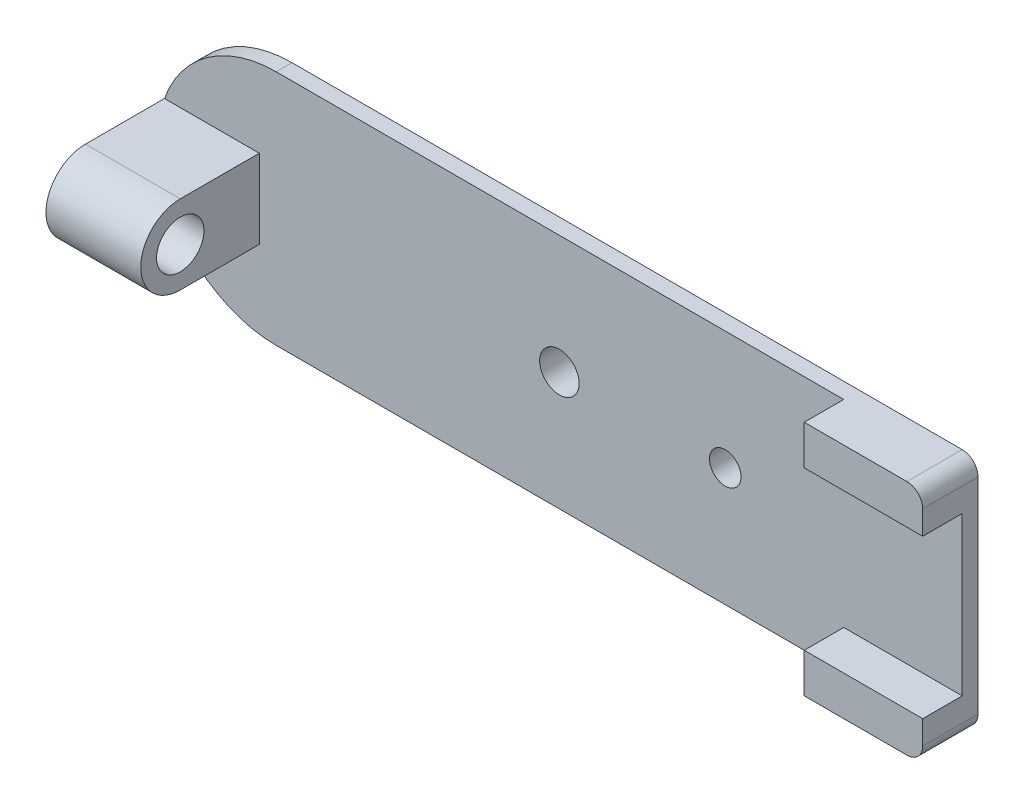
SolidWorks part; units mm, degrees
ref_plane "FACE" through (0, 0, 0) normal (0, 0, 1) x (1, 0, 0)
ref_plane "DESSSUS" through (0, 0, 0) normal (0, 1, 0) x (1, 0, 0)
ref_plane "DROITE" through (0, 0, 0) normal (1, 0, 0) x (0, 0, -1)
sketch "Esquisse1" plane through (0, 0, 0) normal (0, 0, 1) x (1, 0, 0)
  line L0 (0, 30) -> (173.7157, 30)
  line L1 (173.7157, 30) -> (173.7157, -30)
  line L2 (173.7157, -30) -> (0, -30)
  line L3 (-28.2843, 10) -> (-28.2843, -10)
  arc A0 (0, 30) -> (-28.2843, 10) centre (0, 0) ccw
  arc A1 (-28.2843, -10) -> (0, -30) centre (0, 0) ccw
  dimension "D1" = 60
  dimension "D2" = 20
  dimension "D3" = 202
extrude "Base-Extrusion" add sketch "Esquisse1" along normal blind 4
sketch "Esquisse2" plane through (0, 0, 4) normal (0, 0, 1) x (1, 0, 0)
  line L0 (173.7157, 30) -> (0, 30) construction
  line L1 (143.7157, 30) -> (173.7157, 30)
  line L2 (143.7157, 30) -> (143.7157, 20)
  line L3 (143.7157, 20) -> (173.7157, 20)
  line L4 (173.7157, 30) -> (173.7157, 20)
  line L5 (173.7157, -30) -> (173.7157, 30) construction
  line L6 (0, -30) -> (173.7157, -30) construction
  line L7 (143.7157, -20) -> (173.7157, -20)
  line L8 (143.7157, -20) -> (143.7157, -30)
  line L9 (143.7157, -30) -> (173.7157, -30)
  line L10 (173.7157, -20) -> (173.7157, -30)
  dimension "D1" = 30
  dimension "D2" = 30
  dimension "D3" = 10
  dimension "D4" = 10
extrude "Boss.-Extru.1" add sketch "Esquisse2" along normal blind 10
sketch "Esquisse3" plane through (0, 0, 0) normal (0, 0, -1) x (-1, 0, 0)
  line L0 (-127, 0) -> (43, 0) construction
  line L1 (-173.7157, -30) -> (-173.7157, 30) construction
  circle A0 centre (-113.7157, 0) radius 8
  circle A1 centre (-71.7157, 0) radius 9
  dimension "D1" = 16
  dimension "D2" = 18
  dimension "D3" = 60
  dimension "D4" = 42
extrude "Boss.-Extru.2" add sketch "Esquisse3" along normal blind 4
sketch "Esquisse4" plane through (0, 0, -4) normal (0, 0, -1) x (-1, 0, 0)
  circle A0 centre (-113.7157, 0) radius 4
  circle A1 centre (-113.7157, 0) radius 8 construction
  dimension "D1" = 8
extrude "Enlèv. mat.-Extru.1" cut sketch "Esquisse4" against normal through all
sketch "Esquisse5" plane through (0, 0, -4) normal (0, 0, -1) x (-1, 0, 0)
  circle A0 centre (-71.7157, 0) radius 5
  circle A1 centre (-71.7157, 0) radius 9 construction
  dimension "D1" = 10
extrude "Enlèv. mat.-Extru.2" cut sketch "Esquisse5" against normal through all
fillet "Congé1" radius 2
fillet "Congé2" radius 4
sketch "Esquisse6" plane through (-28.2843, 0, 0) normal (-1, 0, 0) x (0, 0, 1)
  line L0 (0, 10) -> (24, 10)
  line L1 (0, 10) -> (0, -10)
  line L2 (0, -10) -> (24, -10)
  line L3 (-4, 9) -> (-4, -9) construction
  arc A0 (24, 10) -> (24, -10) centre (24, 0) cw
  circle A1 centre (24, 0) radius 6
  dimension "D2" = 12
  dimension "D1" = 28
extrude "Boss.-Extru.3" add sketch "Esquisse6" against normal blind 24
sketch "Esquisse7" plane through (0, 0, -4) normal (0, 0, -1) x (-1, 0, 0)
  circle A0 centre (-71.7157, 0) radius 5
  circle A1 centre (-71.7157, 0) radius 9
  circle A2 centre (-71.7157, 0) radius 5 construction
  dimension "D1" = 10
  dimension "D2" = 18
extrude "Boss.-Extru.4" add sketch "Esquisse7" along normal blind 10
